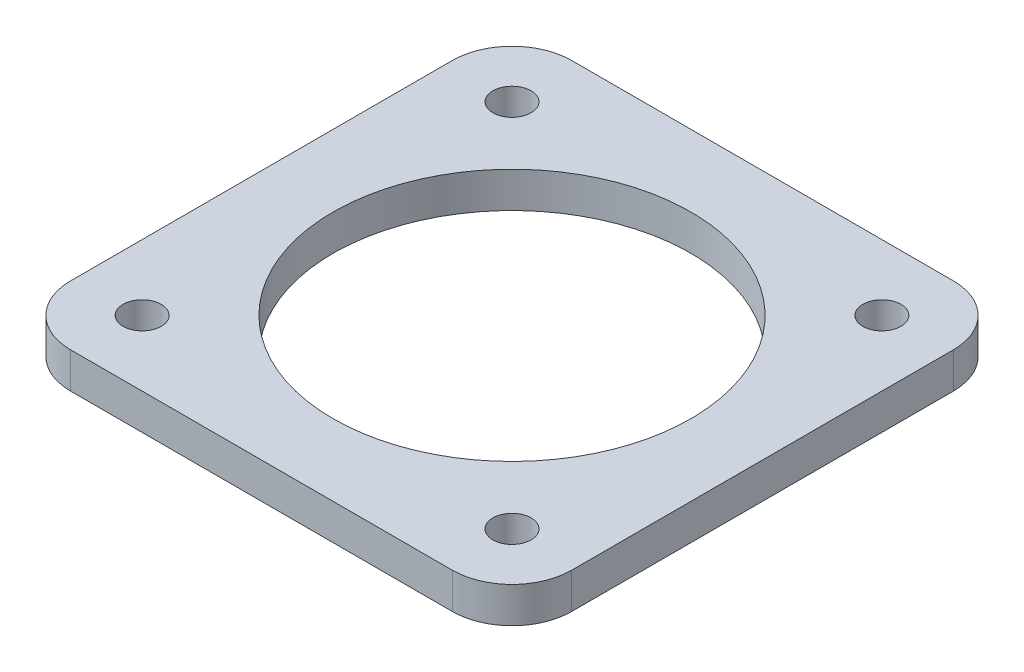
SolidWorks part; units mm, degrees
ref_plane "前视基准面" through (0, 0, 0) normal (0, 0, 1) x (1, 0, 0)
ref_plane "上视基准面" through (0, 0, 0) normal (0, 1, 0) x (1, 0, 0)
ref_plane "右视基准面" through (0, 0, 0) normal (1, 0, 0) x (0, 0, -1)
other "Configuration Table"
sketch "草图1" plane through (0, 0, 0) normal (0, 1, 0) x (1, 0, 0)
  line L1 (-15.5, -15.5) -> (15.5, -15.5)
  line L2 (-15.5, -15.5) -> (-15.5, 15.5)
  line L3 (-15.5, 15.5) -> (15.5, 15.5)
  line L4 (15.5, -15.5) -> (15.5, 15.5)
  line L5 (-15.5, -15.5) -> (15.5, 15.5) construction
  line L6 (-15.5, 15.5) -> (15.5, -15.5) construction
  line L7 (-21, -21) -> (21, -21)
  line L8 (-21, -21) -> (-21, 21)
  line L9 (-21, 21) -> (21, 21)
  line L10 (21, -21) -> (21, 21)
  line L11 (-21, -21) -> (21, 21) construction
  line L12 (-21, 21) -> (21, -21) construction
  circle A0 centre (-15.5, 15.5) radius 1.6
  circle A1 centre (15.5, 15.5) radius 1.6
  circle A2 centre (15.5, -15.5) radius 1.6
  circle A3 centre (-15.5, -15.5) radius 1.6
  circle A4 centre (0.145, -0.145) radius 11
  point P0 (0, 0)
  point P6 (0, 0)
  point P21 (0, 0)
  dimension "D5" = 3.2
  dimension "D7" = 22
  dimension "D1" = 31
  dimension "D2" = 31
  dimension "D3" = 42
  dimension "D4" = 42
  dimension "D6" = 4
extrude "凸台-拉伸1" add sketch "草图1" along normal blind 3 contours A3 L1 A2 L4 A1 L3 A0 L2 A4 | L7 L10 L9 L8 A3 L2 A0 L3 A1 L4 A2 L1
sketch "草图2" plane through (0, 3, 0) normal (0, 1, 0) x (1, 0, 0)
  circle A0 centre (0, 0) radius 15
  dimension "D1" = 30
extrude "切除-拉伸1" cut sketch "草图2" against normal through all
fillet "圆角1" radius 5 4 edges at (21, 1.5, -21) (21, 1.5, 21) (-21, 1.5, 21) (-21, 1.5, -21)
